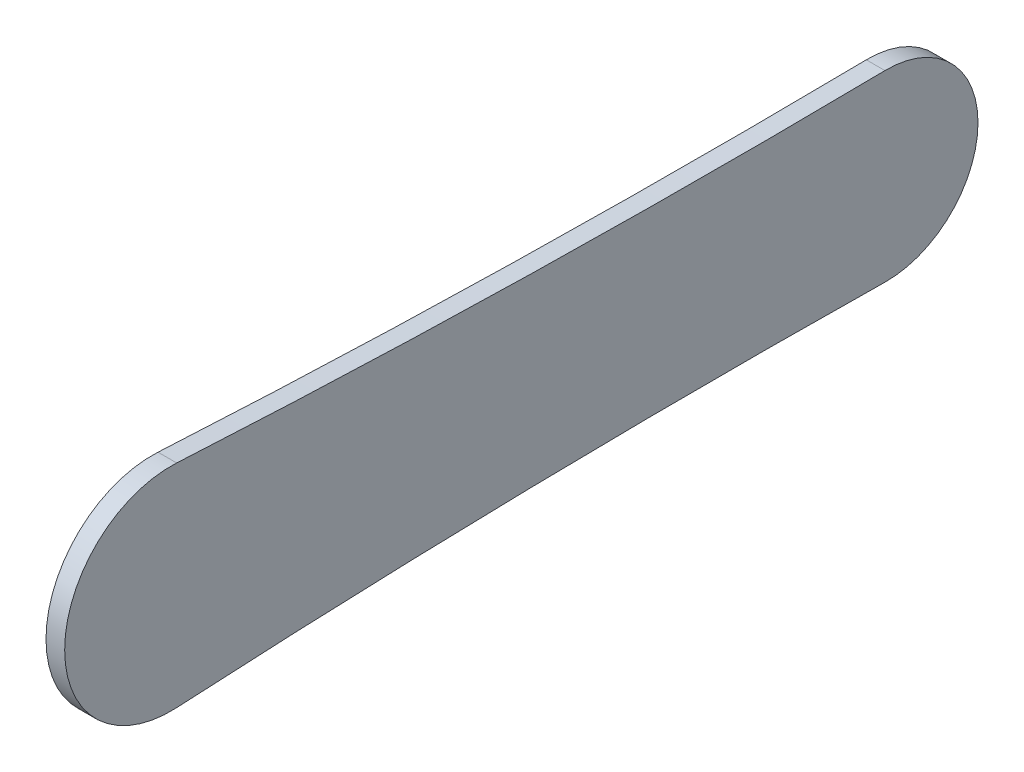
SolidWorks part; units mm, degrees
ref_plane "Front Plane" through (0, 0, 0) normal (0, 0, 1) x (1, 0, 0)
ref_plane "Top Plane" through (0, 0, 0) normal (0, 1, 0) x (1, 0, 0)
ref_plane "Right Plane" through (0, 0, 0) normal (1, 0, 0) x (0, 0, -1)
sketch "Sketch1" plane through (0, 0, 0) normal (1, 0, 0) x (0, 0, -1)
  arc A5 (-22.1828, 30.1743) -> (91.6439, 27.8736) centre (67.1653, 1633.687) ccw
  arc A6 (91.6439, -1.5819) -> (91.6439, 27.8736) centre (91.8684, 13.1458) ccw
  arc A7 (91.6439, -1.5819) -> (-22.1828, -3.8826) centre (67.1653, -1607.3953) ccw
  arc A8 (-22.1828, 30.1743) -> (-22.1828, -3.8826) centre (-23.1316, 13.1458) ccw
  arc A9 (-22.1828, 30.1743) -> (91.6439, 27.8736) centre (67.1653, 1633.687) ccw
  arc A10 (91.6439, -1.5819) -> (91.6439, 27.8736) centre (91.8684, 13.1458) ccw
  arc A11 (91.6439, -1.5819) -> (-22.1828, -3.8826) centre (67.1653, -1607.3953) ccw
  arc A12 (-22.1828, 30.1743) -> (-22.1828, -3.8826) centre (-23.1316, 13.1458) ccw
  dimension "D1" = 0
extrude "Boss-Extrude1" add sketch "Sketch1" along normal blind 3
